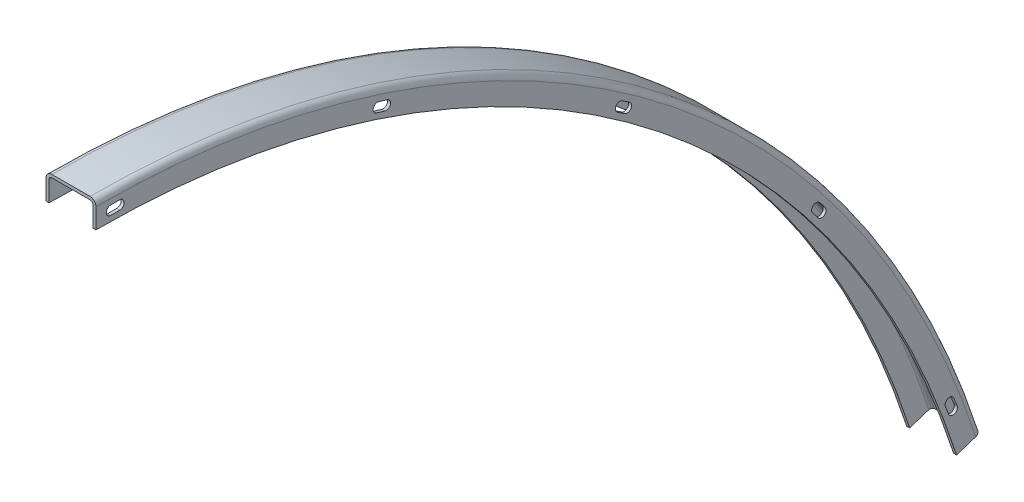
SolidWorks part; units mm, degrees
material "ASTM A36 Steel"
ref_plane "Front Plane" through (0, 0, 0) normal (0, 0, 1) x (1, 0, 0)
ref_plane "Top Plane" through (0, 0, 0) normal (0, 1, 0) x (1, 0, 0)
ref_plane "Right Plane" through (0, 0, 0) normal (1, 0, 0) x (0, 0, -1)
sketch "Sketch1" plane through (0, 0, 0) normal (0, 0, 1) x (1, 0, 0)
  line L0 (6.8425, 105.3307) -> (-44.1575, 105.3307)
  line L1 (-52.1575, 97.3307) -> (-52.1575, 70.3307)
  line L2 (-52.1575, 70.3307) -> (-48.1575, 70.3307)
  line L3 (-48.1575, 70.3307) -> (-48.1575, 97.3307)
  line L4 (-44.1575, 101.3307) -> (6.8425, 101.3307)
  line L5 (10.8425, 97.3307) -> (10.8425, 70.3307)
  line L6 (10.8425, 70.3307) -> (14.8425, 70.3307)
  line L7 (14.8425, 70.3307) -> (14.8425, 97.3307)
  line L8 (14.8425, -1144.6693) -> (-71.0301, -1144.6693)
  arc A0 (-48.1575, 97.3307) -> (-44.1575, 101.3307) centre (-44.1575, 97.3307) cw
  arc A1 (10.8425, 97.3307) -> (6.8425, 101.3307) centre (6.8425, 97.3307) ccw
  arc A2 (14.8425, 97.3307) -> (6.8425, 105.3307) centre (6.8425, 97.3307) ccw
  arc A3 (-52.1575, 97.3307) -> (-44.1575, 105.3307) centre (-44.1575, 97.3307) cw
  point P14 (14.8425, 105.3307)
  point P17 (-52.1575, 105.3307)
  dimension "D7" = 4
  dimension "D8" = 8
  dimension "D1" = 67
  dimension "D2" = 35
  dimension "D3" = 35
  dimension "D4" = 4
  dimension "D5" = 4
  dimension "D6" = 4
  dimension "D9" = 1250
revolve "Revolve1" add sketch "Sketch1" angle 72 about L8
sketch "Sketch2" plane through (14.8425, 0, 0) normal (1, 0, 0) x (0, 0, -1)
  line L0 (20, 83.3307) -> (32, 83.3307) construction
  line L1 (20, 89.3307) -> (32, 89.3307)
  line L2 (20, 77.3307) -> (32, 77.3307)
  line L3 (378.1585, 23.8255) -> (389.6342, 20.3171) construction
  line L4 (379.9128, 29.5633) -> (391.3884, 26.0549)
  line L5 (376.4043, 18.0877) -> (387.88, 14.5792)
  line L6 (703.2696, -137.795) -> (713.2181, -144.5053) construction
  line L7 (706.6248, -132.8208) -> (716.5732, -139.5311)
  line L8 (699.9145, -142.7692) -> (709.8629, -149.4796)
  line L9 (966.9216, -387.4068) -> (974.4735, -396.7325) construction
  line L10 (971.5845, -383.6308) -> (979.1364, -392.9566)
  line L11 (962.2588, -391.1827) -> (969.8106, -400.5084)
  line L12 (1146.0739, -703.1961) -> (1150.5692, -714.3223) construction
  line L13 (1151.637, -700.9484) -> (1156.1323, -712.0746)
  line L14 (1140.5108, -705.4437) -> (1145.0061, -716.5699)
  line L15 (0, -1144.6693) -> (20, 83.3307) construction
  line L16 (0, -1144.6693) -> (378.1585, 23.8255) construction
  arc A0 (20, 89.3307) -> (20, 77.3307) centre (20, 83.3307) ccw
  arc A1 (32, 77.3307) -> (32, 89.3307) centre (32, 83.3307) ccw
  arc A3 (379.9128, 29.5633) -> (376.4043, 18.0877) centre (378.1585, 23.8255) ccw
  arc A4 (387.88, 14.5792) -> (391.3884, 26.0549) centre (389.6342, 20.3171) ccw
  arc A5 (706.6248, -132.8208) -> (699.9145, -142.7692) centre (703.2696, -137.795) ccw
  arc A6 (709.8629, -149.4796) -> (716.5732, -139.5311) centre (713.2181, -144.5053) ccw
  arc A7 (971.5845, -383.6308) -> (962.2588, -391.1827) centre (966.9216, -387.4068) ccw
  arc A8 (969.8106, -400.5084) -> (979.1364, -392.9566) centre (974.4735, -396.7325) ccw
  arc A9 (1151.637, -700.9484) -> (1140.5108, -705.4437) centre (1146.0739, -703.1961) ccw
  arc A10 (1145.0061, -716.5699) -> (1156.1323, -712.0746) centre (1150.5692, -714.3223) ccw
  point P2 (26, 83.3307)
  point P12 (383.8964, 22.0713)
  point P15 (1162.974, -744.2252)
  point P20 (708.2439, -141.1502)
  point P28 (970.6976, -392.0696)
  point P35 (1148.3215, -708.7592)
  dimension "D1" = 13
  dimension "D2" = 20
  dimension "D3" = 12
  dimension "D4" = 5
  dimension "D5" = 17
  dimension "D6" = 1228.1629
extrude "Cut-Extrude1" cut sketch "Sketch2" against normal blind 10
